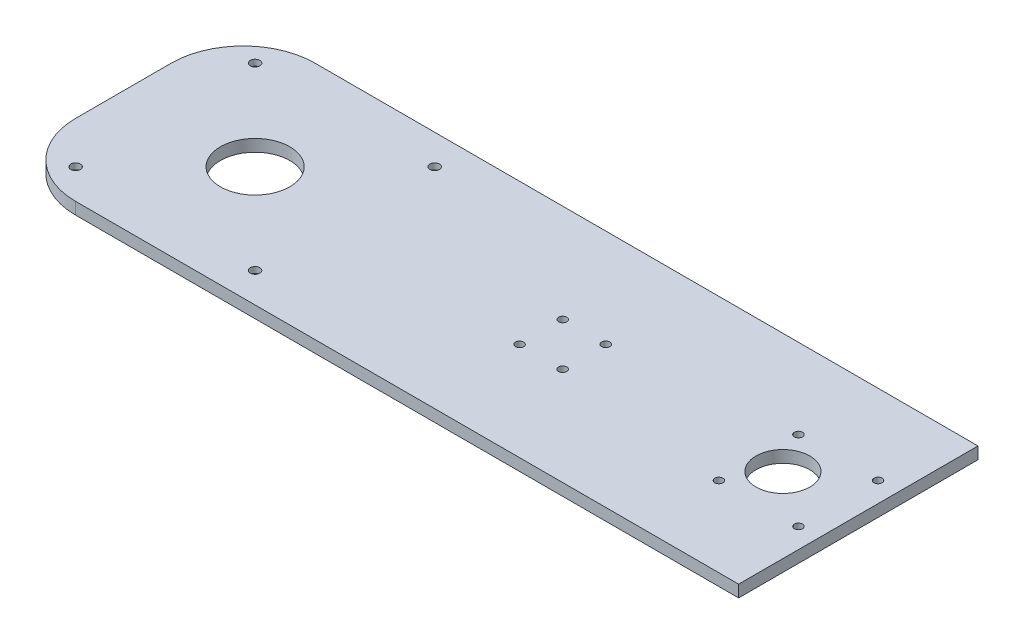
SolidWorks part; units mm, degrees
material "AISI 304"
ref_plane "前视基准面" through (0, 0, 0) normal (0, 0, 1) x (1, 0, 0)
ref_plane "上视基准面" through (0, 0, 0) normal (0, 1, 0) x (1, 0, 0)
ref_plane "右视基准面" through (0, 0, 0) normal (1, 0, 0) x (0, 0, -1)
sketch "Sketch1" plane through (0, 0, 0) normal (0, 1, 0) x (1, 0, 0)
  line L1 (307, -100) -> (-307, -100)
  line L2 (307, -100) -> (307, 100)
  line L3 (307, 100) -> (-307, 100)
  line L4 (-307, -100) -> (-307, 100)
  line L5 (307, -100) -> (-307, 100) construction
  line L6 (307, 100) -> (-307, -100) construction
  point P0 (0, 0)
  dimension "D1" = 200
  dimension "D2" = 614
extrude "Extrude1" add sketch "Sketch1" along normal blind 10
sketch "Sketch2" plane through (0, 10, 0) normal (0, 1, 0) x (1, 0, 0)
  line L0 (-197, 75) -> (-197, -75) construction
  line L1 (-122, -75) -> (-272, -75) construction
  line L2 (-122, -75) -> (-122, 75) construction
  line L3 (-122, 75) -> (-272, 75) construction
  line L4 (-272, -75) -> (-272, 75) construction
  line L5 (-122, -75) -> (-272, 75) construction
  line L6 (-122, 75) -> (-272, -75) construction
  line L7 (-122, 0) -> (-272, 0) construction
  line L8 (-307, 100) -> (-307, -100) construction
  circle A0 centre (-197, 0) radius 29
  circle A1 centre (-272, 75) radius 4
  circle A2 centre (-122, 75) radius 4
  circle A3 centre (-122, -75) radius 4
  circle A4 centre (-272, -75) radius 4
  dimension "D1" = 58
  dimension "D4" = 8
  dimension "D2" = 150
  dimension "D3" = 150
  dimension "D5" = 110
extrude "Extrude2" cut sketch "Sketch2" against normal blind 10
sketch "Sketch3" plane through (0, 10, 0) normal (0, 1, 0) x (1, 0, 0)
  line L0 (307, 0) -> (0, 0) construction
  line L1 (78, -18) -> (42, -18) construction
  line L2 (78, -18) -> (78, 18) construction
  line L3 (78, 18) -> (42, 18) construction
  line L4 (42, -18) -> (42, 18) construction
  line L5 (78, -18) -> (42, 18) construction
  line L6 (78, 18) -> (42, -18) construction
  line L7 (307, -100) -> (307, 100) construction
  line L9 (290.234, -33.234) -> (223.766, -33.234) construction
  line L10 (290.234, -33.234) -> (290.234, 33.234) construction
  line L11 (290.234, 33.234) -> (223.766, 33.234) construction
  line L12 (223.766, -33.234) -> (223.766, 33.234) construction
  line L13 (290.234, -33.234) -> (223.766, 33.234) construction
  line L14 (290.234, 33.234) -> (223.766, -33.234) construction
  circle A0 centre (257, 0) radius 47 construction
  point P0 (60, 0)
  dimension "D4" = 94
  dimension "D5" = 50
  dimension "D1" = 36
  dimension "D2" = 36
  dimension "D3" = 60
hole_wizard "M8 Tapped Hole2" positions "3DSketch2" profile "Sketch5" tap size "M8" standard "GB"
sketch3d "3DSketch2"
  point P0 (223.766, 10, -33.234)
  point P3 (290.234, 10, -33.234)
  point P6 (223.766, 10, 33.234)
  point P9 (290.234, 10, 33.234)
sketch "Sketch5" plane through (223.766, 10, -33.234) normal (1, 0, 0) x (0, 0, 1)
  line L0 (0, 0) -> (0, 21.7929)
  line L1 (0, 21.7929) -> (3.4, 19.75)
  line L2 (3.4, 19.75) -> (3.4, 0)
  line L5 (3.4, 0) -> (0, 0)
  line L10 (0, 21.7929) -> (-3.4, 19.75) construction
  line L11 (0, -6.35) -> (0, 107.95) construction
  dimension "螺纹孔钻头直径" = 6.8
  dimension "螺纹孔钻头深度" = 19.75
  dimension "导头角度" = 118
sketch "Sketch6" plane through (0, 10, 0) normal (0, 1, 0) x (1, 0, 0)
  circle A0 centre (244, 0) radius 22.5
  dimension "D1" = 45
  dimension "D2" = 13
extrude "Extrude3" cut sketch "Sketch6" against normal blind 10
sketch "Sketch7" plane through (0, 0, 0) normal (0, -1, 0) x (1, 0, 0)
  circle A5 centre (-272, 75) radius 9
  circle A6 centre (-272, 75) radius 9
  dimension "D1" = 5
extrude "Extrude4" cut sketch "Sketch7" against normal blind 5
pattern_linear "LPattern1" count 2 spacing 150 along (1, 0, 0) count 2 spacing 150 along (0, 0, -1) of "Extrude4"
hole_wizard "M8 Tapped Hole3" positions "3DSketch6" profile "Sketch11" tap size "M8" standard "GB"
sketch3d "3DSketch6"
  point P0 (42, 10, -18)
  point P3 (78, 10, -18)
  point P6 (42, 10, 18)
  point P9 (78, 10, 18)
sketch "Sketch11" plane through (42, 10, -18) normal (1, 0, 0) x (0, 0, 1)
  line L0 (0, 0) -> (0, 21.7929)
  line L1 (0, 21.7929) -> (3.4, 19.75)
  line L2 (3.4, 19.75) -> (3.4, 0)
  line L5 (3.4, 0) -> (0, 0)
  line L10 (0, 21.7929) -> (-3.4, 19.75) construction
  line L11 (0, -6.35) -> (0, 107.95) construction
  dimension "螺纹孔钻头直径" = 6.8
  dimension "螺纹孔钻头深度" = 19.75
  dimension "导头角度" = 118
fillet "Fillet1" radius 60 2 edges at (-307, 5, 100) (-307, 5, -100)
